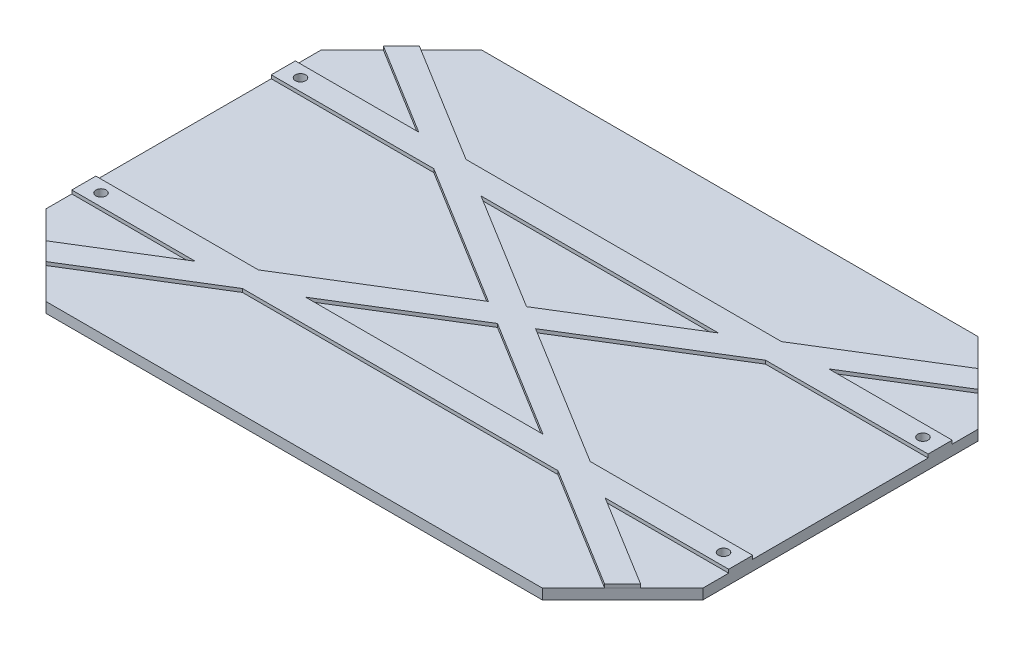
SolidWorks part; units mm, degrees
material "3.0205 (EN-AW 1200)"
ref_plane "Alzado" through (0, 0, 0) normal (0, 0, 1) x (1, 0, 0)
ref_plane "Planta" through (0, 0, 0) normal (0, 1, 0) x (1, 0, 0)
ref_plane "Vista lateral" through (0, 0, 0) normal (1, 0, 0) x (0, 0, -1)
sketch "Croquis1" plane through (0, 0, 0) normal (0, 1, 0) x (1, 0, 0)
  line L0 (0, 0) -> (95.4995, 0) construction
  line L1 (-72.165, -63.3345) -> (72.165, -63.3345)
  line L2 (-95.4995, -40) -> (-95.4995, 40)
  line L3 (-95.4995, 40) -> (-72.165, 63.3345)
  line L4 (95.4995, 0) -> (-95.4995, 0) construction
  line L5 (-72.165, 63.3345) -> (72.165, 63.3345)
  line L6 (95.4995, 40) -> (72.165, 63.3345)
  line L8 (-95.4995, -40) -> (-72.165, -63.3345)
  line L10 (95.4995, -40) -> (72.165, -63.3345)
  line L12 (95.4995, 40) -> (95.4995, -40)
  point P0 (0, 0)
  dimension "D1" = 33
  dimension "D2" = 135
  dimension "D3" = 144.33
  dimension "D4" = 135
  dimension "D5" = 72.165
  dimension "D6" = 80
  dimension "D7" = 135
extrude "Saliente-Extruir1" add sketch "Croquis1" along normal blind 3
sketch "Croquis2" plane through (0, 3, 0) normal (0, 1, 0) x (1, 0, 0)
  line L0 (-95.4995, 0) -> (95.4995, 0) construction
  line L1 (-95.4995, 40) -> (-95.4995, -40) construction
  line L2 (95.4995, -40) -> (95.4995, 40) construction
  line L3 (0, 63.3345) -> (0, 4.2287) construction
  line L4 (-95.4995, -32.5) -> (-59.5991, -32.5)
  line L5 (-95.4995, -32.5) -> (-95.4995, -25.5)
  line L6 (-95.4995, -25.5) -> (-48.2403, -25.5)
  line L7 (95.4995, -32.5) -> (95.4995, -25.5)
  line L8 (72.165, 63.3345) -> (-72.165, 63.3345) construction
  line L9 (-72.165, -63.3345) -> (72.165, -63.3345) construction
  line L10 (0, 0) -> (0, -63.3345) construction
  line L11 (-95.4995, -40) -> (-72.165, -63.3345) construction
  line L12 (-34.516, -25.5) -> (34.5166, -25.5)
  line L13 (72.165, -63.3345) -> (95.4995, -40) construction
  line L14 (-81.2182, -54.2813) -> (-86.4486, -49.0464)
  line L15 (95.4995, 32.5) -> (95.4995, 25.5)
  line L16 (-81.2182, -54.2813) -> (-45.8746, -32.5)
  line L17 (0, -4.2287) -> (34.5166, -25.5)
  line L18 (-86.4486, -49.0464) -> (-59.5991, -32.5)
  line L19 (6.8619, 0) -> (48.2396, -25.5)
  line L20 (-95.4995, 32.5) -> (-95.4995, 25.5)
  line L21 (81.2159, -54.2791) -> (87.2217, -48.2779)
  line L22 (-81.2182, 54.2813) -> (-86.4486, 49.0464)
  line L23 (81.2159, 54.2791) -> (87.2217, 48.2779)
  line L24 (-48.2403, 25.5) -> (-6.8619, 0)
  line L25 (59.5982, -32.5) -> (95.4995, -32.5)
  line L26 (48.2396, -25.5) -> (95.4995, -25.5)
  line L27 (45.8754, -32.5) -> (81.2159, -54.2791)
  line L28 (59.5982, -32.5) -> (86.4506, -49.0484)
  line L29 (-34.516, -25.5) -> (0, -4.2287)
  line L30 (-34.516, 25.5) -> (0, 4.2287)
  line L32 (-48.2403, -25.5) -> (-6.8619, 0)
  line L33 (-45.8746, -32.5) -> (45.8754, -32.5)
  line L34 (-86.4486, 49.0464) -> (-59.5991, 32.5)
  line L35 (-81.2182, 54.2813) -> (-45.8746, 32.5)
  line L36 (-95.4995, 25.5) -> (-48.2403, 25.5)
  line L37 (-95.4995, 32.5) -> (-59.5991, 32.5)
  line L38 (59.5982, 32.5) -> (86.4506, 49.0484)
  line L39 (45.8754, 32.5) -> (81.2159, 54.2791)
  line L40 (48.2396, 25.5) -> (95.4995, 25.5)
  line L41 (59.5982, 32.5) -> (95.4995, 32.5)
  line L42 (-45.8746, 32.5) -> (45.8754, 32.5)
  line L43 (6.8619, 0) -> (48.2396, 25.5)
  line L44 (0, 4.2287) -> (34.5166, 25.5)
  line L45 (-34.516, 25.5) -> (34.5166, 25.5)
  line M2 (-72.165, 63.3345) -> (-95.4995, 40)
  line M3 (-95.4995, 40) -> (-95.4995, -40)
  line M4 (-95.4995, -40) -> (-72.165, -63.3345)
  line M6 (72.165, -63.3345) -> (95.4995, -40)
  line M7 (95.4995, -40) -> (95.4995, 40)
  dimension "D1" = 7.5
  dimension "D2" = 7
extrude "Saliente-Extruir2" add sketch "Croquis2" along normal blind 1 contours L19 L43 L40 L41 L38 L23 L39 L42 L35 L34 L37 L36 L24 L32 L6 L4 L18 L16 L33 L27 L28 L25 L26 L12 L29 L17 L30 L45 L44 M7 M2 M3 M4 M6
sketch "Croquis3" plane through (0, 4, 0) normal (0, 1, 0) x (1, 0, 0)
  line L0 (-95.4995, -29) -> (95.4995, -29) construction
  line L1 (-95.4995, -25.5) -> (-95.4995, -32.5) construction
  line L2 (95.4995, -32.5) -> (95.4995, -25.5) construction
  circle A0 centre (-90.4995, -29) radius 1.5
  dimension "D1" = 3
  dimension "D2" = 5
extrude "Cortar-Extruir1" cut sketch "Croquis3" against normal through all
sketch "Croquis5" plane through (0, 4, 0) normal (0, 1, 0) x (1, 0, 0)
  line L0 (0, 63.3345) -> (0, -63.3345)
  line L1 (72.165, 63.3345) -> (-72.165, 63.3345) construction
  line L2 (-72.165, -63.3345) -> (72.165, -63.3345) construction
  line L3 (-95.4995, 0) -> (95.4995, 0)
  line L4 (-95.4995, 25.5) -> (-95.4995, -25.5) construction
  line L5 (95.4995, -25.5) -> (95.4995, 25.5) construction
  circle A0 centre (-90.4995, -29) radius 1.5
  circle A1 centre (90.4995, -29) radius 1.5
  circle A2 centre (-90.4995, 29) radius 1.5
  circle A3 centre (90.4995, 29) radius 1.5
extrude "Cortar-Extruir2" cut sketch "Croquis5" against normal through all contours A2 | A3 | A1
